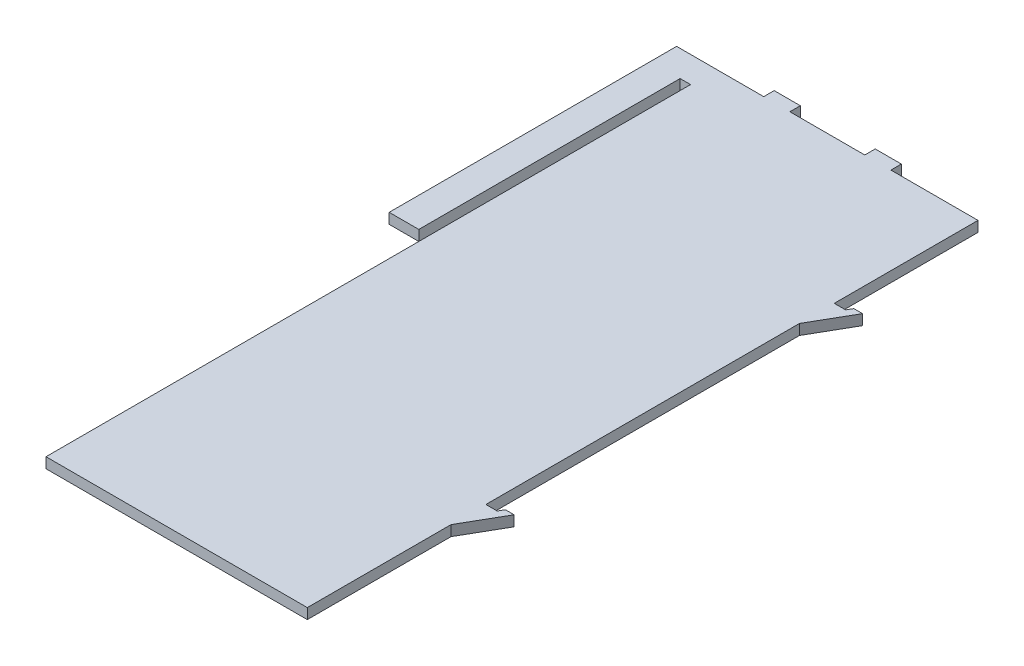
SolidWorks part; units mm, degrees
ref_plane "Front Plane" through (0, 0, 0) normal (0, 0, 1) x (1, 0, 0)
ref_plane "Top Plane" through (0, 0, 0) normal (0, 1, 0) x (1, 0, 0)
ref_plane "Right Plane" through (0, 0, 0) normal (1, 0, 0) x (0, 0, -1)
sketch "Sketch1" plane through (0, 0, 0) normal (0, 1, 0) x (1, 0, 0)
  line L0 (0, 0) -> (0, 165)
  line L3 (173, -220) -> (23, -220)
  line L4 (0, 0) -> (17, 0)
  line L5 (17, 0) -> (17, 150)
  line L6 (17, 150) -> (23, 150)
  line L7 (23, 150) -> (23, -220)
  line L13 (65, 171) -> (65, 165)
  line L14 (65, 165) -> (108, 165)
  line L15 (108, 165) -> (108, 171)
  line L17 (65, 171) -> (50, 171)
  line L18 (50, 171) -> (50, 165)
  line L19 (50, 165) -> (0, 165)
  line L20 (108, 171) -> (123, 171)
  line L21 (173, 82.5) -> (179.5, 82.5)
  line L22 (123, 171) -> (123, 165)
  line L23 (123, 165) -> (173, 165)
  line L24 (179.5, 82.5) -> (181.225, 85.5)
  line L25 (181.225, 85.5) -> (186.225, 85.5)
  line L26 (186.225, 85.5) -> (173, 62.5)
  line L28 (173, -117.5) -> (179.5, -117.5)
  line L29 (179.5, -117.5) -> (181.225, -114.5)
  line L30 (181.225, -114.5) -> (186.225, -114.5)
  line L31 (186.225, -114.5) -> (173, -137.5)
  line L33 (173, 165) -> (173, 82.5)
  line L34 (173, 62.5) -> (173, -117.5)
  line L35 (173, -137.5) -> (173, -220)
  dimension "D1" = 6
  dimension "D2" = 15
  dimension "D3" = 150
  dimension "D4" = 370
  dimension "D5" = 150
  dimension "D6" = 17
  dimension "D7" = 15
  dimension "D10" = 50
  dimension "D11" = 6
  dimension "D12" = 6.5
  dimension "D13" = 5
  dimension "D14" = 20
  dimension "D15" = 3
  dimension "D16" = 6.5
  dimension "D17" = 5
  dimension "D18" = 20
  dimension "D19" = 3
  dimension "D20" = 200
extrude "Boss-Extrude1" add sketch "Sketch1" along normal blind 6
